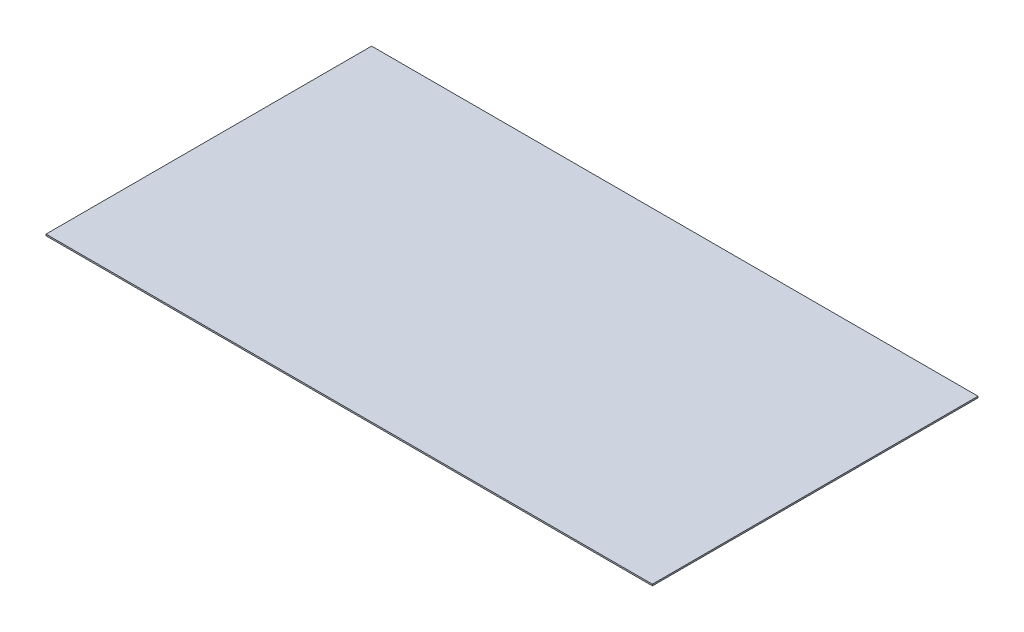
SolidWorks part; units mm, degrees
ref_plane "Alzado" through (0, 0, 0) normal (0, 0, 1) x (1, 0, 0)
ref_plane "Planta" through (0, 0, 0) normal (0, 1, 0) x (1, 0, 0)
ref_plane "Vista lateral" through (0, 0, 0) normal (1, 0, 0) x (0, 0, -1)
sketch "Croquis1" plane through (0, 0, 0) normal (0, 1, 0) x (1, 0, 0)
  line L1 (-406, 218) -> (406, 218)
  line L2 (-406, 218) -> (-406, -218)
  line L3 (-406, -218) -> (406, -218)
  line L4 (406, 218) -> (406, -218)
  dimension "D1" = 218
  dimension "D2" = 218
  dimension "D3" = 406
  dimension "D4" = 406
extrude "Saliente-Extruir1" add sketch "Croquis1" along normal blind 2
